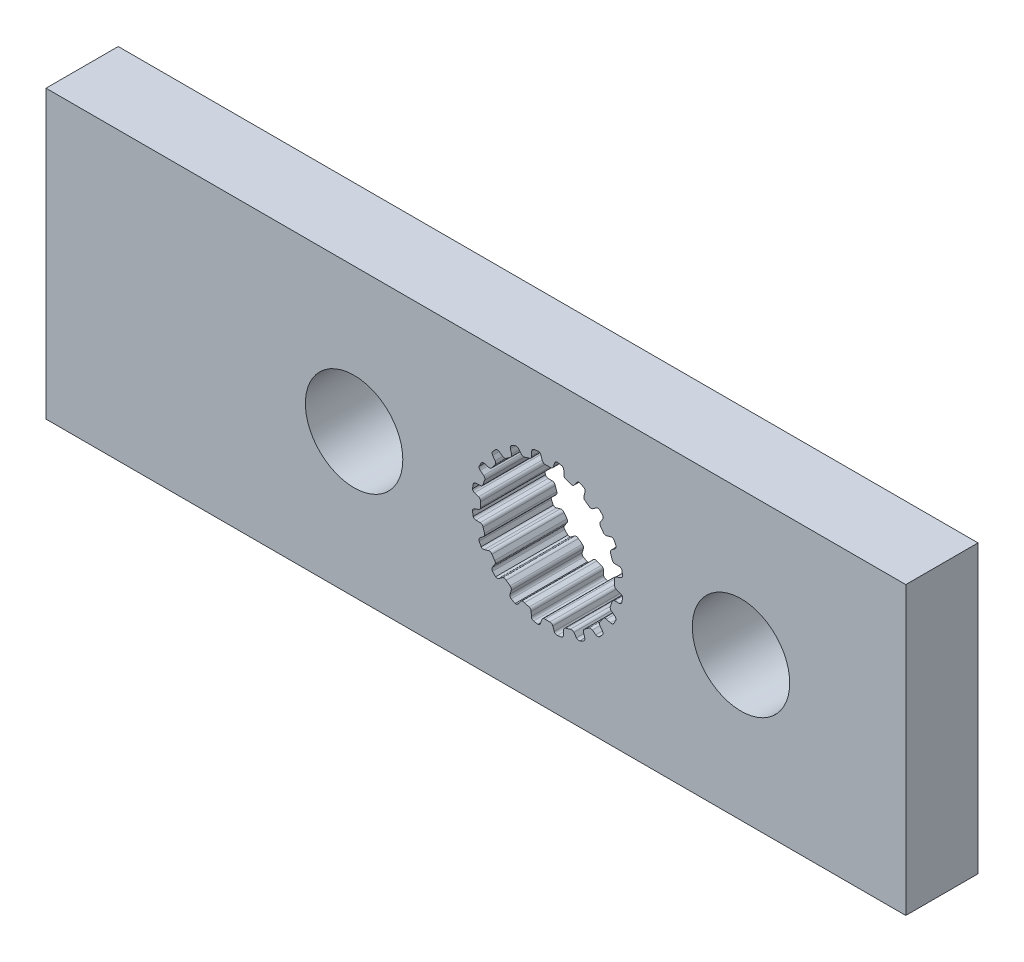
SolidWorks part; units mm, degrees
ref_plane "Front Plane" through (0, 0, 0) normal (0, 0, 1) x (1, 0, 0)
ref_plane "Top Plane" through (0, 0, 0) normal (0, 1, 0) x (1, 0, 0)
ref_plane "Right Plane" through (0, 0, 0) normal (1, 0, 0) x (0, 0, -1)
sketch "Sketch1" plane through (0, 0, 0) normal (0, 0, 1) x (1, 0, 0)
  line L0 (-0.1069, 2.9699) -> (0.1069, 2.9699)
  line L1 (0.3159, 3.2375) -> (0.2537, 3.0575)
  line L2 (-0.2964, 3.2367) -> (-0.2318, 3.0575)
  line L3 (-0.2964, 3.2367) -> (0.3159, 3.2375) construction
  line L4 (0, 3.3252) -> (0, 0) construction
  line L5 (-0.2318, 3.0575) -> (0.2537, 3.0575) construction
  line L6 (-0.4281, 3.3241) -> (0.4281, 3.3263) construction
  line L7 (0.7183, 3.1698) -> (0.7244, 2.9795)
  line L8 (0.816, 2.8576) -> (1.0195, 2.7915)
  line L9 (1.3009, 2.9815) -> (1.1862, 2.8295)
  line L10 (1.6627, 2.7927) -> (1.6097, 2.6099)
  line L11 (1.6591, 2.4655) -> (1.8322, 2.3398)
  line L12 (2.1585, 2.4335) -> (2.0025, 2.3245)
  line L13 (2.4443, 2.1423) -> (2.3374, 1.9847)
  line L14 (2.3398, 1.8322) -> (2.4655, 1.6591)
  line L15 (2.8049, 1.6474) -> (2.6228, 1.5919)
  line L16 (2.9866, 1.2821) -> (2.8363, 1.1653)
  line L17 (2.7915, 1.0195) -> (2.8576, 0.816)
  line L18 (3.1767, 0.7) -> (2.9863, 0.7035)
  line L19 (3.2367, 0.2964) -> (3.0575, 0.2318)
  line L20 (2.9699, 0.1069) -> (2.9699, -0.1069)
  line L21 (3.2375, -0.3159) -> (3.0575, -0.2537)
  line L22 (3.1698, -0.7183) -> (2.9795, -0.7244)
  line L23 (2.8576, -0.816) -> (2.7915, -1.0195)
  line L24 (2.9815, -1.3009) -> (2.8295, -1.1862)
  line L25 (2.7927, -1.6627) -> (2.6099, -1.6097)
  line L26 (2.4655, -1.6591) -> (2.3398, -1.8322)
  line L27 (2.4335, -2.1585) -> (2.3245, -2.0025)
  line L28 (2.1423, -2.4443) -> (1.9847, -2.3374)
  line L29 (1.8322, -2.3398) -> (1.6591, -2.4655)
  line L30 (1.6474, -2.8049) -> (1.5919, -2.6228)
  line L31 (1.2821, -2.9866) -> (1.1653, -2.8363)
  line L32 (1.0195, -2.7915) -> (0.816, -2.8576)
  line L33 (0.7, -3.1767) -> (0.7035, -2.9863)
  line L34 (0.2964, -3.2367) -> (0.2318, -3.0575)
  line L35 (0.1069, -2.9699) -> (-0.1069, -2.9699)
  line L36 (-0.3159, -3.2375) -> (-0.2537, -3.0575)
  line L37 (-0.7183, -3.1698) -> (-0.7244, -2.9795)
  line L38 (-0.816, -2.8576) -> (-1.0195, -2.7915)
  line L39 (-1.3009, -2.9815) -> (-1.1862, -2.8295)
  line L40 (-1.6627, -2.7927) -> (-1.6097, -2.6099)
  line L41 (-1.6591, -2.4655) -> (-1.8322, -2.3398)
  line L42 (-2.1585, -2.4335) -> (-2.0025, -2.3245)
  line L43 (-2.4443, -2.1423) -> (-2.3374, -1.9847)
  line L44 (-2.3398, -1.8322) -> (-2.4655, -1.6591)
  line L45 (-2.8049, -1.6474) -> (-2.6228, -1.5919)
  line L46 (-2.9866, -1.2821) -> (-2.8363, -1.1653)
  line L47 (-2.7915, -1.0195) -> (-2.8576, -0.816)
  line L48 (-3.1767, -0.7) -> (-2.9863, -0.7035)
  line L49 (-3.2367, -0.2964) -> (-3.0575, -0.2318)
  line L50 (-2.9699, -0.1069) -> (-2.9699, 0.1069)
  line L51 (-3.2375, 0.3159) -> (-3.0575, 0.2537)
  line L52 (-3.1698, 0.7183) -> (-2.9795, 0.7244)
  line L53 (-2.8576, 0.816) -> (-2.7915, 1.0195)
  line L54 (-2.9815, 1.3009) -> (-2.8295, 1.1862)
  line L55 (-2.7927, 1.6627) -> (-2.6099, 1.6097)
  line L56 (-2.4655, 1.6591) -> (-2.3398, 1.8322)
  line L57 (-2.4335, 2.1585) -> (-2.3245, 2.0025)
  line L58 (-2.1423, 2.4443) -> (-1.9847, 2.3374)
  line L59 (-1.8322, 2.3398) -> (-1.6591, 2.4655)
  line L60 (-1.6474, 2.8049) -> (-1.5919, 2.6228)
  line L61 (-1.2821, 2.9866) -> (-1.1653, 2.8363)
  line L62 (-1.0195, 2.7915) -> (-0.816, 2.8576)
  line L63 (-0.7, 3.1767) -> (-0.7035, 2.9863)
  line L64 (0.4281, 3.3263) -> (0.62, 3.2938)
  line L65 (1.4351, 3.0312) -> (1.6075, 2.9409)
  line L66 (2.3015, 2.4394) -> (2.4376, 2.3003)
  line L67 (2.9427, 1.6088) -> (3.0291, 1.4344)
  line L68 (3.2958, 0.6207) -> (3.3241, 0.4281)
  line L69 (3.3263, -0.4281) -> (3.2938, -0.62)
  line L70 (3.0312, -1.4351) -> (2.9409, -1.6075)
  line L71 (2.4394, -2.3015) -> (2.3003, -2.4376)
  line L72 (1.6088, -2.9427) -> (1.4344, -3.0291)
  line L73 (0.6207, -3.2958) -> (0.4281, -3.3241)
  line L74 (-0.4281, -3.3263) -> (-0.62, -3.2938)
  line L75 (-1.4351, -3.0312) -> (-1.6075, -2.9409)
  line L76 (-2.3015, -2.4394) -> (-2.4376, -2.3003)
  line L77 (-2.9427, -1.6088) -> (-3.0291, -1.4344)
  line L78 (-3.2958, -0.6207) -> (-3.3241, -0.4281)
  line L79 (-3.3263, 0.4281) -> (-3.2938, 0.62)
  line L80 (-3.0312, 1.4351) -> (-2.9409, 1.6075)
  line L81 (-2.4394, 2.3015) -> (-2.3003, 2.4376)
  line L82 (-1.6088, 2.9427) -> (-1.4344, 3.0291)
  line L83 (-0.6207, 3.2958) -> (-0.4281, 3.3241)
  line L84 (0, 0) -> (0, -6.35) construction
  line L85 (-22.225, 6.35) -> (15.875, 6.35)
  line L86 (-22.225, 6.35) -> (-22.225, -6.35)
  line L87 (-22.225, -6.35) -> (15.875, -6.35)
  line L88 (15.875, 6.35) -> (15.875, -6.35)
  line L89 (-8.5725, 0) -> (8.5725, 0) construction
  arc A0 (0.2537, 3.0575) -> (0.1069, 2.9699) centre (0.1283, 3.1009) cw
  arc A1 (-0.2318, 3.0575) -> (-0.1069, 2.9699) centre (-0.1069, 3.1026) ccw
  arc A2 (0.62, 3.2938) -> (0.7183, 3.1698) centre (0.5856, 3.1656) cw
  arc A3 (0.7244, 2.9795) -> (0.816, 2.8576) centre (0.857, 2.9838) ccw
  arc A4 (-0.4281, 3.3241) -> (-0.2964, 3.2367) centre (-0.4213, 3.1916) cw
  arc A5 (0.4281, 3.3263) -> (0.3159, 3.2375) centre (0.4413, 3.1942) ccw
  arc A6 (1.1862, 2.8295) -> (1.0195, 2.7915) centre (1.0802, 2.9095) cw
  arc A7 (1.4351, 3.0312) -> (1.3009, 2.9815) centre (1.4068, 2.9015) ccw
  arc A8 (1.6075, 2.9409) -> (1.6627, 2.7927) centre (1.5352, 2.8297) cw
  arc A9 (1.6097, 2.6099) -> (1.6591, 2.4655) centre (1.7371, 2.5729) ccw
  arc A10 (2.0025, 2.3245) -> (1.8322, 2.3398) centre (1.9264, 2.4332) cw
  arc A11 (2.3015, 2.4394) -> (2.1585, 2.4335) centre (2.2346, 2.3248) ccw
  arc A12 (2.4376, 2.3003) -> (2.4443, 2.1423) centre (2.3345, 2.2168) cw
  arc A13 (2.3374, 1.9847) -> (2.3398, 1.8322) centre (2.4472, 1.9102) ccw
  arc A14 (2.6228, 1.5919) -> (2.4655, 1.6591) centre (2.5841, 1.7189) cw
  arc A15 (2.9427, 1.6088) -> (2.8049, 1.6474) centre (2.8436, 1.5205) ccw
  arc A16 (3.0291, 1.4344) -> (2.9866, 1.2821) centre (2.9052, 1.3869) cw
  arc A17 (2.8363, 1.1653) -> (2.7915, 1.0195) centre (2.9177, 1.0605) ccw
  arc A18 (2.9863, 0.7035) -> (2.8576, 0.816) centre (2.9887, 0.8362) cw
  arc A19 (3.2958, 0.6207) -> (3.1767, 0.7) centre (3.1743, 0.5673) ccw
  arc A20 (3.3241, 0.4281) -> (3.2367, 0.2964) centre (3.1916, 0.4213) cw
  arc A21 (3.0575, 0.2318) -> (2.9699, 0.1069) centre (3.1026, 0.1069) ccw
  arc A22 (3.0575, -0.2537) -> (2.9699, -0.1069) centre (3.1009, -0.1283) cw
  arc A23 (3.3263, -0.4281) -> (3.2375, -0.3159) centre (3.1942, -0.4413) ccw
  arc A24 (3.2938, -0.62) -> (3.1698, -0.7183) centre (3.1656, -0.5856) cw
  arc A25 (2.9795, -0.7244) -> (2.8576, -0.816) centre (2.9838, -0.857) ccw
  arc A26 (2.8295, -1.1862) -> (2.7915, -1.0195) centre (2.9095, -1.0802) cw
  arc A27 (3.0312, -1.4351) -> (2.9815, -1.3009) centre (2.9015, -1.4068) ccw
  arc A28 (2.9409, -1.6075) -> (2.7927, -1.6627) centre (2.8297, -1.5352) cw
  arc A29 (2.6099, -1.6097) -> (2.4655, -1.6591) centre (2.5729, -1.7371) ccw
  arc A30 (2.3245, -2.0025) -> (2.3398, -1.8322) centre (2.4332, -1.9264) cw
  arc A31 (2.4394, -2.3015) -> (2.4335, -2.1585) centre (2.3248, -2.2346) ccw
  arc A32 (2.3003, -2.4376) -> (2.1423, -2.4443) centre (2.2168, -2.3345) cw
  arc A33 (1.9847, -2.3374) -> (1.8322, -2.3398) centre (1.9102, -2.4472) ccw
  arc A34 (1.5919, -2.6228) -> (1.6591, -2.4655) centre (1.7189, -2.5841) cw
  arc A35 (1.6088, -2.9427) -> (1.6474, -2.8049) centre (1.5205, -2.8436) ccw
  arc A36 (1.4344, -3.0291) -> (1.2821, -2.9866) centre (1.3869, -2.9052) cw
  arc A37 (1.1653, -2.8363) -> (1.0195, -2.7915) centre (1.0605, -2.9177) ccw
  arc A38 (0.7035, -2.9863) -> (0.816, -2.8576) centre (0.8362, -2.9887) cw
  arc A39 (0.6207, -3.2958) -> (0.7, -3.1767) centre (0.5673, -3.1743) ccw
  arc A40 (0.4281, -3.3241) -> (0.2964, -3.2367) centre (0.4213, -3.1916) cw
  arc A41 (0.2318, -3.0575) -> (0.1069, -2.9699) centre (0.1069, -3.1026) ccw
  arc A42 (-0.2537, -3.0575) -> (-0.1069, -2.9699) centre (-0.1283, -3.1009) cw
  arc A43 (-0.4281, -3.3263) -> (-0.3159, -3.2375) centre (-0.4413, -3.1942) ccw
  arc A44 (-0.62, -3.2938) -> (-0.7183, -3.1698) centre (-0.5856, -3.1656) cw
  arc A45 (-0.7244, -2.9795) -> (-0.816, -2.8576) centre (-0.857, -2.9838) ccw
  arc A46 (-1.1862, -2.8295) -> (-1.0195, -2.7915) centre (-1.0802, -2.9095) cw
  arc A47 (-1.4351, -3.0312) -> (-1.3009, -2.9815) centre (-1.4068, -2.9015) ccw
  arc A48 (-1.6075, -2.9409) -> (-1.6627, -2.7927) centre (-1.5352, -2.8297) cw
  arc A49 (-1.6097, -2.6099) -> (-1.6591, -2.4655) centre (-1.7371, -2.5729) ccw
  arc A50 (-2.0025, -2.3245) -> (-1.8322, -2.3398) centre (-1.9264, -2.4332) cw
  arc A51 (-2.3015, -2.4394) -> (-2.1585, -2.4335) centre (-2.2346, -2.3248) ccw
  arc A52 (-2.4376, -2.3003) -> (-2.4443, -2.1423) centre (-2.3345, -2.2168) cw
  arc A53 (-2.3374, -1.9847) -> (-2.3398, -1.8322) centre (-2.4472, -1.9102) ccw
  arc A54 (-2.6228, -1.5919) -> (-2.4655, -1.6591) centre (-2.5841, -1.7189) cw
  arc A55 (-2.9427, -1.6088) -> (-2.8049, -1.6474) centre (-2.8436, -1.5205) ccw
  arc A56 (-3.0291, -1.4344) -> (-2.9866, -1.2821) centre (-2.9052, -1.3869) cw
  arc A57 (-2.8363, -1.1653) -> (-2.7915, -1.0195) centre (-2.9177, -1.0605) ccw
  arc A58 (-2.9863, -0.7035) -> (-2.8576, -0.816) centre (-2.9887, -0.8362) cw
  arc A59 (-3.2958, -0.6207) -> (-3.1767, -0.7) centre (-3.1743, -0.5673) ccw
  arc A60 (-3.3241, -0.4281) -> (-3.2367, -0.2964) centre (-3.1916, -0.4213) cw
  arc A61 (-3.0575, -0.2318) -> (-2.9699, -0.1069) centre (-3.1026, -0.1069) ccw
  arc A62 (-3.0575, 0.2537) -> (-2.9699, 0.1069) centre (-3.1009, 0.1283) cw
  arc A63 (-3.3263, 0.4281) -> (-3.2375, 0.3159) centre (-3.1942, 0.4413) ccw
  arc A64 (-3.2938, 0.62) -> (-3.1698, 0.7183) centre (-3.1656, 0.5856) cw
  arc A65 (-2.9795, 0.7244) -> (-2.8576, 0.816) centre (-2.9838, 0.857) ccw
  arc A66 (-2.8295, 1.1862) -> (-2.7915, 1.0195) centre (-2.9095, 1.0802) cw
  arc A67 (-3.0312, 1.4351) -> (-2.9815, 1.3009) centre (-2.9015, 1.4068) ccw
  arc A68 (-2.9409, 1.6075) -> (-2.7927, 1.6627) centre (-2.8297, 1.5352) cw
  arc A69 (-2.6099, 1.6097) -> (-2.4655, 1.6591) centre (-2.5729, 1.7371) ccw
  arc A70 (-2.3245, 2.0025) -> (-2.3398, 1.8322) centre (-2.4332, 1.9264) cw
  arc A71 (-2.4394, 2.3015) -> (-2.4335, 2.1585) centre (-2.3248, 2.2346) ccw
  arc A72 (-2.3003, 2.4376) -> (-2.1423, 2.4443) centre (-2.2168, 2.3345) cw
  arc A73 (-1.9847, 2.3374) -> (-1.8322, 2.3398) centre (-1.9102, 2.4472) ccw
  arc A74 (-1.5919, 2.6228) -> (-1.6591, 2.4655) centre (-1.7189, 2.5841) cw
  arc A75 (-1.6088, 2.9427) -> (-1.6474, 2.8049) centre (-1.5205, 2.8436) ccw
  arc A76 (-1.4344, 3.0291) -> (-1.2821, 2.9866) centre (-1.3869, 2.9052) cw
  arc A77 (-1.1653, 2.8363) -> (-1.0195, 2.7915) centre (-1.0605, 2.9177) ccw
  arc A78 (-0.7035, 2.9863) -> (-0.816, 2.8576) centre (-0.8362, 2.9887) cw
  arc A79 (-0.6207, 3.2958) -> (-0.7, 3.1767) centre (-0.5673, 3.1743) ccw
  circle A80 centre (0, 0) radius 12.7 construction
  circle A81 centre (0, 0) radius 5.08 construction
  circle A82 centre (-8.5725, 0) radius 2.159
  circle A83 centre (8.5725, 0) radius 2.159
  point P14 (0, 2.9699)
  point P247 (0, 0)
  dimension "D4" = 0.1327
  dimension "D8" = 20
  dimension "D9" = 25.4
  dimension "D13" = 10.16
  dimension "D16" = 4.318
  dimension "D1" = 2.9699
  dimension "D2" = 0.2139
  dimension "D3" = 0.1904
  dimension "D5" = 0.0877
  dimension "D6" = 0.4855
  dimension "D7" = 0.8563
  dimension "D10" = 12.7
  dimension "D11" = 38.1
  dimension "D12" = 6.35
  dimension "D14" = 15.875
  dimension "D15" = 17.145
extrude "Boss-Extrude1" add sketch "Sketch1" along normal mid plane 3.2004
